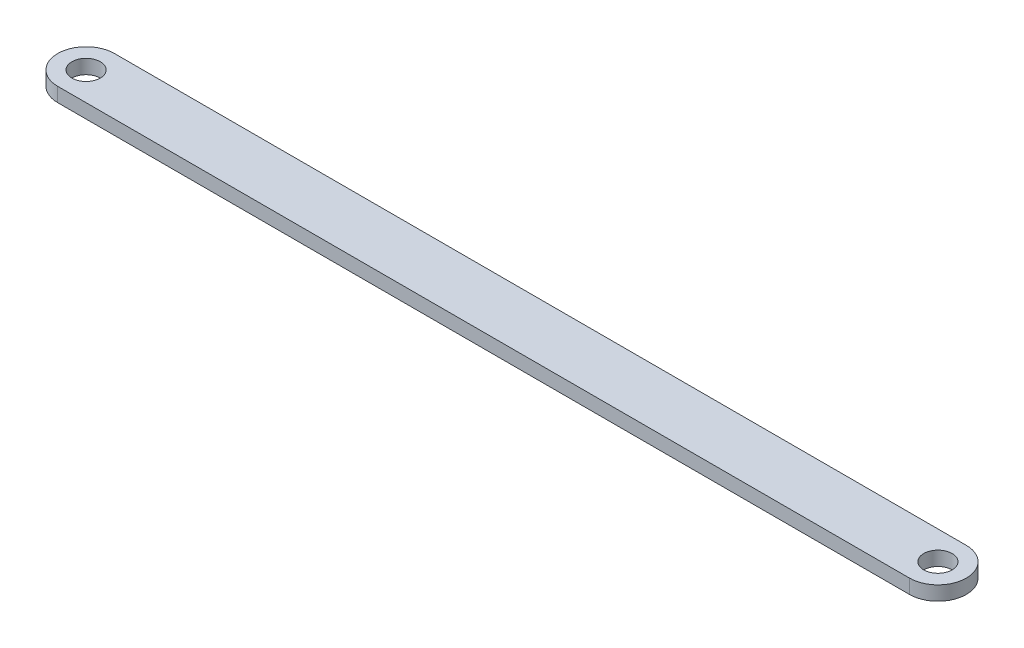
SolidWorks part; units mm, degrees
ref_plane "Ön Düzlem" through (0, 0, 0) normal (0, 0, 1) x (1, 0, 0)
ref_plane "Üst Düzlem" through (0, 0, 0) normal (0, 1, 0) x (1, 0, 0)
ref_plane "Sağ Düzlem" through (0, 0, 0) normal (1, 0, 0) x (0, 0, -1)
sketch "Sketch1" plane through (0, 0, 0) normal (0, 1, 0) x (1, 0, 0)
  line L0 (-150, 0) -> (150, 0) construction
  line L1 (-150, 10) -> (150, 10)
  line L2 (-150, -10) -> (150, -10)
  arc A0 (-150, 10) -> (-150, -10) centre (-150, 0) ccw
  arc A1 (150, -10) -> (150, 10) centre (150, 0) ccw
  circle A2 centre (-150, 0) radius 5
  circle A3 centre (150, 0) radius 5
  point P2 (0, 0)
  dimension "D1" = 10
  dimension "D3" = 10
  dimension "D4" = 10
  dimension "D2" = 300
extrude "Boss-Extrude1" add sketch "Sketch1" along normal blind 5
